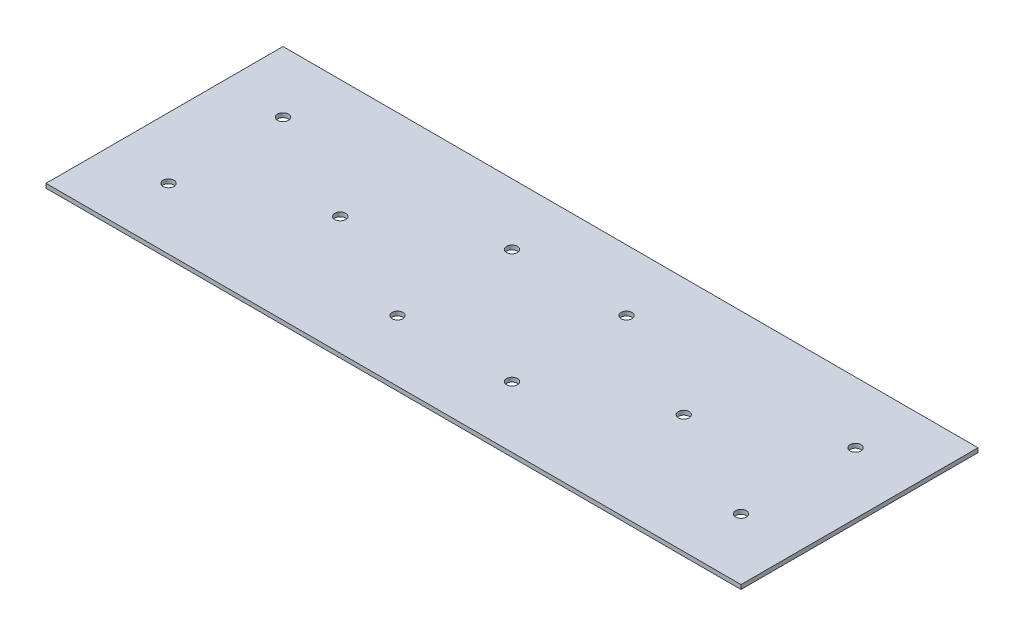
SolidWorks part; units mm, degrees
ref_plane "Front Plane" through (0, 0, 0) normal (0, 0, 1) x (1, 0, 0)
ref_plane "Top Plane" through (0, 0, 0) normal (0, 1, 0) x (1, 0, 0)
ref_plane "Right Plane" through (0, 0, 0) normal (1, 0, 0) x (0, 0, -1)
sketch "Sketch1" plane through (0, 0, 0) normal (0, 1, 0) x (1, 0, 0)
  line L1 (0, 0) -> (261, 0)
  line L2 (0, 0) -> (0, 89)
  line L3 (0, 89) -> (261, 89)
  line L4 (261, 0) -> (261, 89)
  dimension "D1" = 261
  dimension "D2" = 89
extrude "Boss-Extrude1" add sketch "Sketch1" along normal blind 1.6
ref_plane "Plane1" through (0, 0, -44.5) normal (0, 0, 1) x (1, 0, 0)
ref_plane "Plane2" through (130.5, 0, 0) normal (1, 0, 0) x (0, 0, -1)
sketch "Sketch3" plane through (0, 1.6, 0) normal (0, 1, 0) x (1, 0, 0)
  circle A0 centre (23, 66) radius 2.05
  circle A1 centre (23, 23) radius 2.05
  circle A2 centre (66, 44.5) radius 2.05
  circle A3 centre (109, 66) radius 2.05
  circle A4 centre (109, 23) radius 2.05
  circle A5 centre (152, 23) radius 2.05
  circle A6 centre (152, 66) radius 2.05
  circle A7 centre (195, 44.5) radius 2.05
  circle A8 centre (238, 66) radius 2.05
  circle A9 centre (238, 23) radius 2.05
  dimension "D1" = 4.1
extrude "Cut-Extrude1" cut sketch "Sketch3" against normal through all
